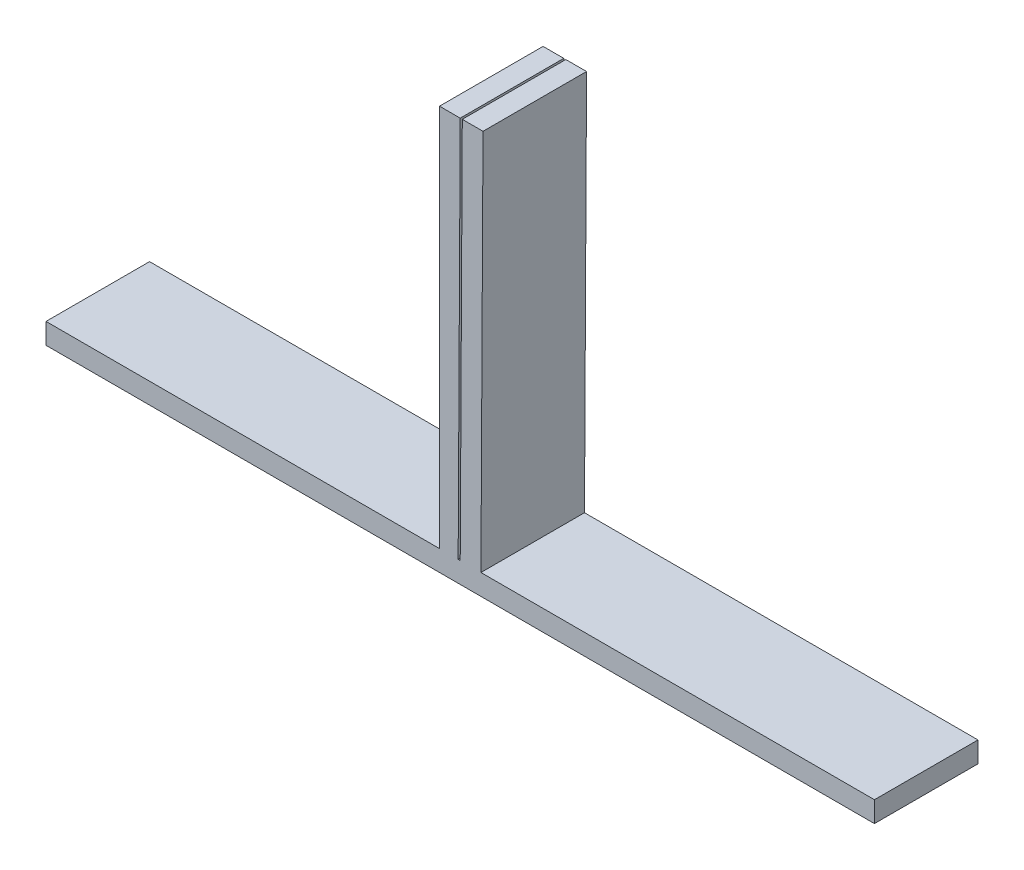
SolidWorks part; units mm, degrees
ref_plane "Plan de face" through (0, 0, 0) normal (0, 0, 1) x (1, 0, 0)
ref_plane "Plan de dessus" through (0, 0, 0) normal (0, 1, 0) x (1, 0, 0)
ref_plane "Plan de droite" through (0, 0, 0) normal (1, 0, 0) x (0, 0, -1)
sketch "Esquisse1" plane through (0, 0, 0) normal (0, 0, 1) x (1, 0, 0)
  line L0 (37.1967, 0) -> (-42.8033, 0)
  line L1 (37.1967, 0) -> (37.1967, 2)
  line L2 (37.1967, 2) -> (-0.8033, 2)
  line L3 (-0.8033, 2) -> (-0.6033, 38.9995)
  line L4 (-0.6033, 38.9995) -> (-2.6033, 39)
  line L5 (-2.6033, 39) -> (-2.8033, 2.0005)
  line L6 (-2.8033, 2.0005) -> (-3.0033, 2.0005)
  line L7 (-3.0033, 2.0005) -> (-2.8033, 39)
  line L8 (-2.8033, 39) -> (-4.8033, 39)
  line L9 (-4.8033, 39) -> (-4.8033, 2)
  line L10 (-4.8033, 2) -> (-42.8033, 2)
  line L11 (-42.8033, 2) -> (-42.8033, 0)
  dimension "D1" = 80
  dimension "D2" = 37
  dimension "D3" = 37
  dimension "D4" = 2
  dimension "D5" = 2
  dimension "D6" = 37
  dimension "D7" = 37
  dimension "D8" = 0.2
  dimension "D9" = 2
  dimension "D10" = 2
  dimension "D11" = 0.2
extrude "Boss.-Extru.1" add sketch "Esquisse1" along normal blind 10
